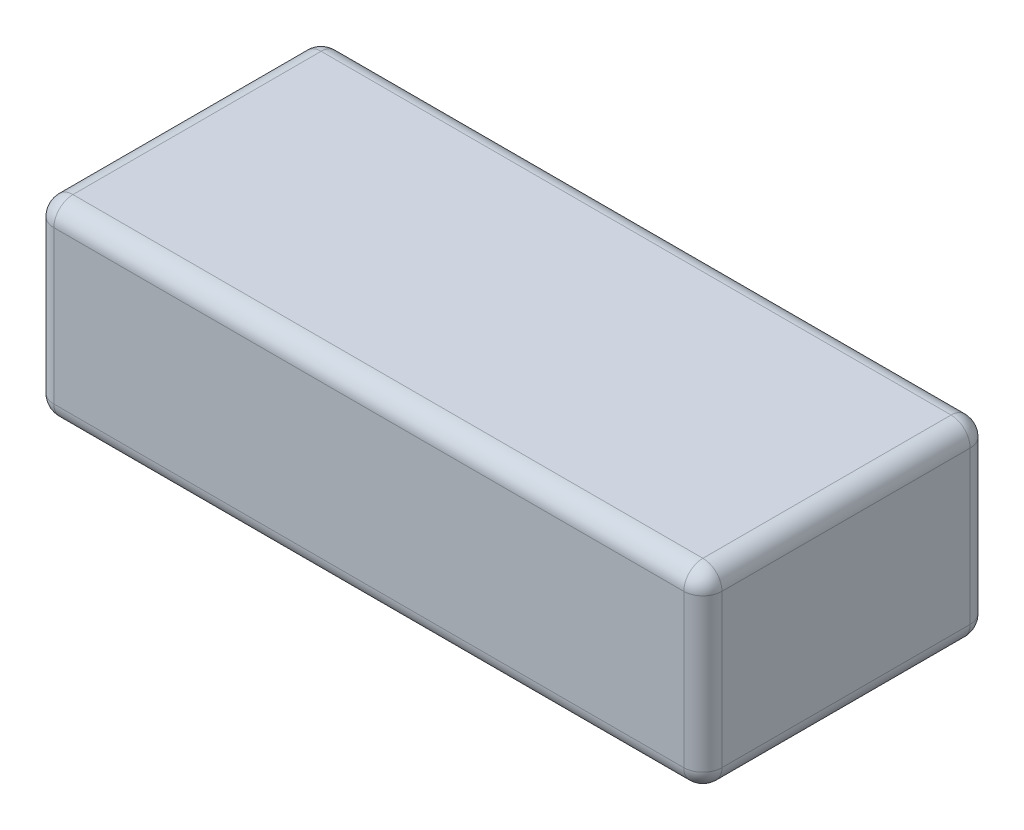
SolidWorks part; units mm, degrees
ref_plane "Front Plane" through (0, 0, 0) normal (0, 0, 1) x (1, 0, 0)
ref_plane "Top Plane" through (0, 0, 0) normal (0, 1, 0) x (1, 0, 0)
ref_plane "Right Plane" through (0, 0, 0) normal (1, 0, 0) x (0, 0, -1)
sketch "Sketch1" plane through (0, 0, 0) normal (0, 1, 0) x (1, 0, 0)
  line L1 (-35, -15) -> (35, -15)
  line L2 (-35, -15) -> (-35, 15)
  line L3 (-35, 15) -> (35, 15)
  line L4 (35, -15) -> (35, 15)
  line L5 (-35, -15) -> (35, 15) construction
  line L6 (-35, 15) -> (35, -15) construction
  point P0 (0, 0)
  dimension "D1" = 70
  dimension "D2" = 30
extrude "Boss-Extrude1" add sketch "Sketch1" along normal blind 20
fillet "Fillet1" radius 2 12 edges at (0, 0, -15) (-35, 0, 0) (0, 0, 15) (35, 0, 0) (0, 20, 15) (-35, 20, 0) (0, 20, -15) (35, 20, 0) (35, 10, -15) (35, 10, 15) (-35, 10, -15) (-35, 10, 15)
